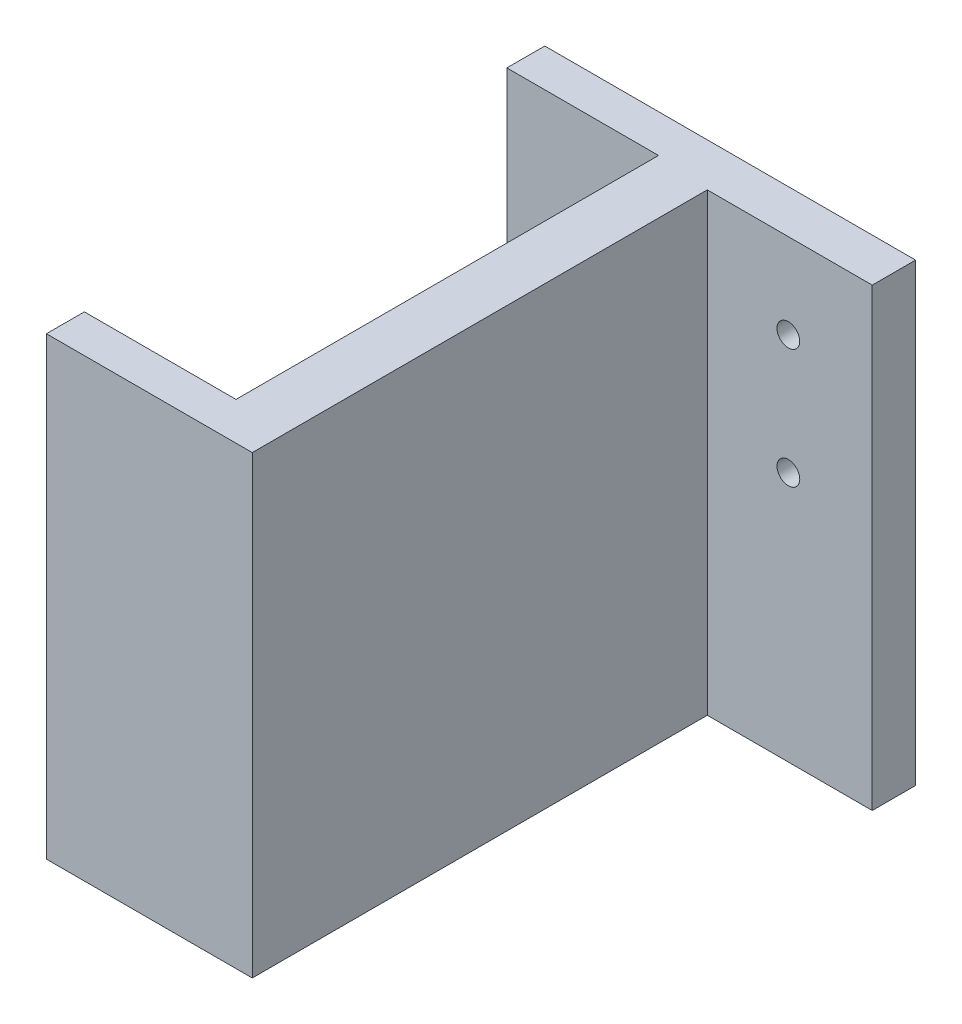
SolidWorks part; units mm, degrees
ref_plane "Front Plane" through (0, 0, 0) normal (0, 0, 1) x (1, 0, 0)
ref_plane "Top Plane" through (0, 0, 0) normal (0, 1, 0) x (1, 0, 0)
ref_plane "Right Plane" through (0, 0, 0) normal (1, 0, 0) x (0, 0, -1)
sketch "Sketch1" plane through (0, 0, 0) normal (0, 1, 0) x (1, 0, 0)
  line L0 (0, 0) -> (0, 32.8571)
  line L1 (0, 32.8571) -> (14.4463, 32.8571)
  line L2 (14.4463, 32.8571) -> (14.4463, 30)
  line L3 (14.4463, 30) -> (3.5714, 30)
  line L4 (3.5714, 30) -> (3.5714, 0)
  line L5 (3.5714, 0) -> (0, 0)
  point P3 (7.2232, 32.8571)
  dimension "D1" = 30
  dimension "D2" = 2.8571
extrude "Boss-Extrude1" add sketch "Sketch1" along normal blind 30
sketch "Sketch3" plane through (0, 0, 0) normal (-1, 0, 0) x (0, 0, 1)
  line L1 (-32.8571, 0) -> (0, 0) construction
  line L2 (-30.3571, 0) -> (-32.8571, 0)
  line L4 (-2.5, 0) -> (0, 0)
  line L5 (-30.3571, 2.5) -> (-2.5, 2.5)
  line L6 (-30.3571, 0) -> (-2.5, 0)
  line L7 (-30.3571, 27.5) -> (-30.3571, 30)
  line L8 (-32.8571, 30) -> (0, 30) construction
  line L9 (-30.3571, 30) -> (-32.8571, 30)
  line L10 (0, 30) -> (0, 0) construction
  line L11 (-2.5, 27.5) -> (-2.5, 30)
  line L12 (-32.8571, 30) -> (-32.8571, 0) construction
  line L14 (-2.5, 2.5) -> (-2.5, 27.5)
  line L15 (-30.3571, 2.5) -> (-2.5, 2.5)
  line L16 (-30.3571, 27.5) -> (-30.3571, 2.5)
  line L17 (-2.5, 27.5) -> (-30.3571, 27.5)
  line L18 (-2.5, 2.5) -> (-2.5, 27.5)
  line L20 (-30.3571, 27.5) -> (-30.3571, 2.5)
  line L22 (0, 30) -> (0, 0)
  line L24 (-32.8571, 30) -> (-32.8571, 0)
  line L26 (-2.5, 30) -> (0, 30)
  dimension "D1" = 2.5
extrude "Boss-Extrude3" add sketch "Sketch3" along normal blind 10
sketch "Sketch4" plane through (0, 0, -30) normal (0, 0, 1) x (1, 0, 0)
  circle A0 centre (8.9171, 24.3963) radius 0.75
  circle A1 centre (8.9171, 16.5263) radius 0.75
  dimension "D1" = 1.5
  dimension "D2" = 1.5
  dimension "D3" = 7.87
extrude "Cut-Extrude1" cut sketch "Sketch4" against normal blind 10
